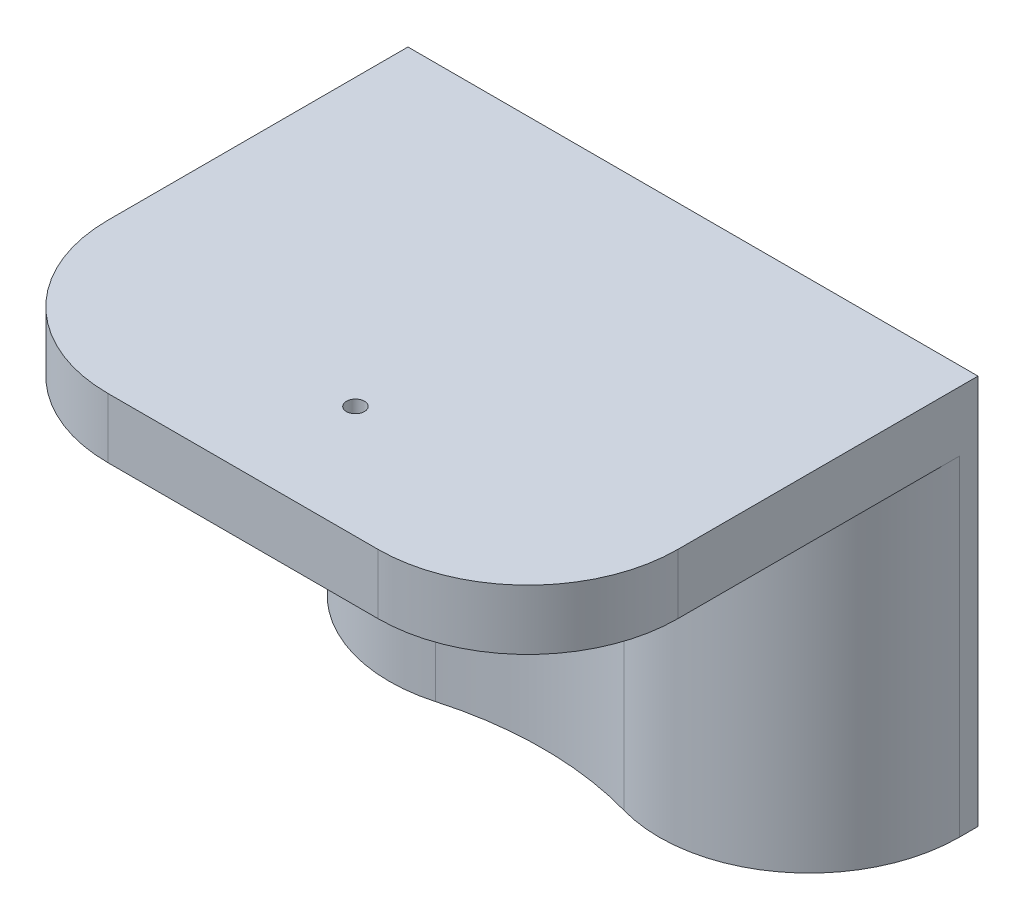
SolidWorks part; units mm, degrees
ref_plane "Alzado" through (0, 0, 0) normal (0, 0, 1) x (1, 0, 0)
ref_plane "Planta" through (0, 0, 0) normal (0, 1, 0) x (1, 0, 0)
ref_plane "Vista lateral" through (0, 0, 0) normal (1, 0, 0) x (0, 0, -1)
sketch "Croquis2" plane through (0, 0, 0) normal (0, 1, 0) x (1, 0, 0)
  line L1 (-43.1071, -17.6252) -> (-5.1071, -17.6252)
  line L2 (-43.1071, -17.6252) -> (-43.1071, -37.6252)
  line L3 (-33.1071, -47.6252) -> (-15.1071, -47.6252)
  line L4 (-5.1071, -17.6252) -> (-5.1071, -37.6252)
  arc A0 (-15.1071, -47.6252) -> (-5.1071, -37.6252) centre (-15.1071, -37.6252) ccw
  arc A1 (-33.1071, -47.6252) -> (-43.1071, -37.6252) centre (-33.1071, -37.6252) cw
  circle A2 centre (-24.1071, -40.1252) radius 0.6
  dimension "D1" = 10
extrude "Saliente-Extruir1" add sketch "Croquis2" along normal blind 4
sketch "Croquis3" plane through (0, 0, 0) normal (0, -1, 0) x (1, 0, 0)
  line L0 (-43.1071, 17.6252) -> (-5.1071, 17.6252)
  line L1 (-43.1071, 17.6252) -> (-43.1071, 37.6252)
  line L3 (-5.1071, 17.6252) -> (-5.1071, 37.6252)
  arc A0 (-43.1071, 37.6252) -> (-5.1071, 37.6252) centre (-24.1071, 50.6752) ccw
extrude "Saliente-Extruir2" add sketch "Croquis3" along normal blind 22
fillet "Redondeo1" radius 10 1 edges at (-43.1071, -11, 37.6252)
fillet "Redondeo2" radius 10 1 edges at (-5.1071, -11, 37.6252)
